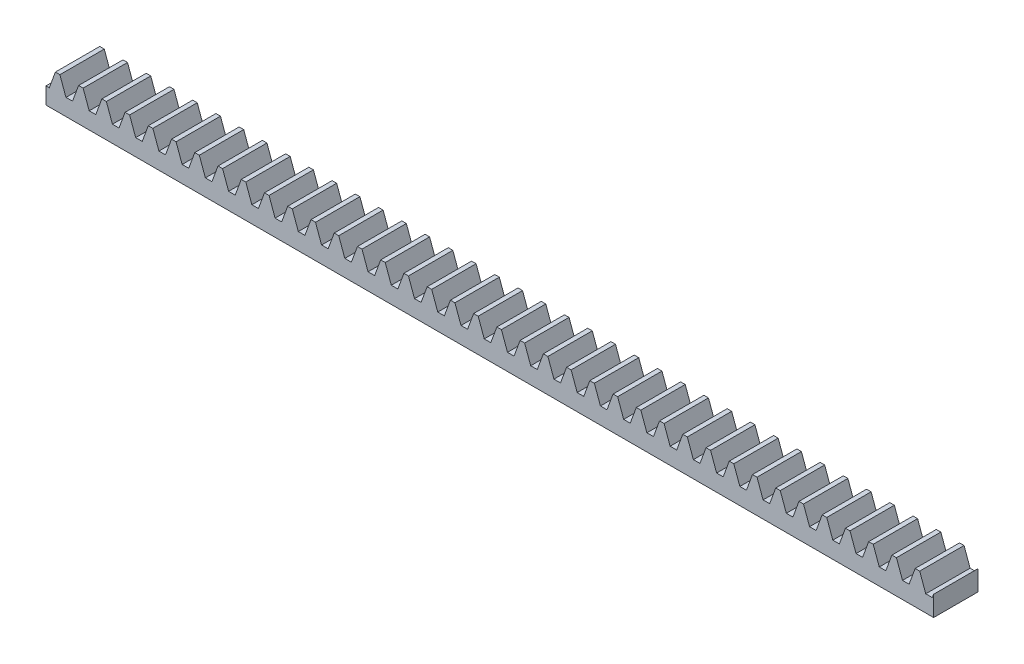
SolidWorks part; units mm, degrees
extrude "Blank" add sketch "BlankSke" against normal blind 6
sketch "BlankSke" plane through (0, 0, 0) normal (0, 0, 1) x (1, 0, 0)
  line L1 (0, 0) -> (120, 0)
  line L2 (0, 0) -> (0, 4.5)
  line L3 (0, 4.5) -> (120, 4.5)
  line L4 (120, 0) -> (120, 4.5)
  dimension "Length" = 120
  dimension "Blank_height" = 4.5
ref_plane "Plane1" through (0, 0, 0) normal (0, 0, 1) x (1, 0, 0)
ref_plane "Plane2" through (0, 0, 0) normal (0, 1, 0) x (1, 0, 0)
ref_plane "Plane3" through (0, 0, 0) normal (1, 0, 0) x (0, 0, -1)
sketch "HoldingSke" plane through (0, 0, 0) normal (0, 1, 0) x (1, 0, 0)
  line L0 (0, 0) -> (0.1392, 0.9903)
  line L1 (-15, 0) -> (100, 0) construction
  line L2 (0, 0) -> (-2.1039, 2.3779)
  line L3 (0, 0) -> (-11.863, 4.5341)
  line L4 (0, 0) -> (6.6156, 5.5511)
  line L5 (0, 0) -> (-23.7986, -8.8762)
  line L6 (0, 0) -> (-10.5278, -7.1032)
  line L9 (-71.009, 38.7566) -> (41.7541, 79.799)
  line L10 (-76.2, 3.3779) -> (-72.7, 3.3779)
  line L11 (0, 0) -> (-6, 0)
  line L12 (-76.2, 101.6) -> (-76.162, 101.6)
  line L13 (24.9733, 27.94) -> (52.9518, 28.4284)
  line L14 (24.9733, 27.94) -> (24.9743, 27.94)
  line L15 (24.9733, 27.94) -> (100.4006, 29.5858)
  circle A0 centre (0, 0) radius 19.05
  circle A1 centre (0, 0) radius 1.75
  circle A2 centre (0, 0) radius 12.7
  dimension "MPH" = 3.5
  dimension "Diameter" = 38.1
  dimension "Num_teeth" = 40
  dimension "Pitch" = 1
  dimension "Show_teeth" = 998
  dimension "Thickness" = 12.7
  dimension "Ap" = 20
  dimension "Pitch_height" = 3.5
  dimension "Width" = 6
  dimension "Backlash" = 0.038
  dimension "Addendum_fac" = 1
  dimension "Dedendum_fac" = 1.25
  dimension "Clearance_fac" = 0.25
  dimension "Dedendum_add" = 0.001
  dimension "Length" = 120
  dimension "Module" = 1
sketch "TooCutSkeIll" plane through (0, 0, 0) normal (0, 0, 1) x (1, 0, 0)
  line L0 (-1.2538, 4.4737) -> (-0.5045, 2.4152)
  line L1 (-0.2687, 2.25) -> (0.2687, 2.25)
  line L2 (0.5045, 2.4152) -> (1.2538, 4.4737)
  line L3 (120, 4.5) -> (0, 4.5) construction
  line L4 (0, 0) -> (0, 64.897) construction
  line L5 (-13.208, 3.5) -> (12.954, 3.5) construction
  line L6 (0, 0) -> (120, 0) construction
  line L7 (0.8994, 3.5) -> (0.8994, 48.7463) construction
  line L8 (-0.8994, 3.5) -> (-0.8994, 48.7463) construction
  line L9 (1.2914, 4.5) -> (1.2914, 4.5254)
  line L10 (-1.2914, 4.5) -> (-1.2914, 4.5254)
  line L11 (-1.2914, 4.5254) -> (1.2914, 4.5254)
  arc A0 (0.2687, 2.25) -> (0.5045, 2.4152) centre (0.2687, 2.501) ccw
  arc A1 (-0.5045, 2.4152) -> (-0.2687, 2.25) centre (-0.2687, 2.501) ccw
  arc A2 (1.2914, 4.5) -> (1.2538, 4.4737) centre (1.2914, 4.46) ccw
  arc A3 (-1.2538, 4.4737) -> (-1.2914, 4.5) centre (-1.2914, 4.46) ccw
  dimension "Pitch_height" = 3.5
  dimension "Addendum_plus" = 1.0254
  dimension "Pressure_angle" = 20
  dimension "Gap_width" = 1.7988
  dimension "Dedendum" = 1.25
extrude "ToothCutIll" [suppressed] cut sketch "TooCutSkeIll" against normal through all
sketch "TooCutSkeSim" plane through (0, 0, 0) normal (0, 0, 1) x (1, 0, 0)
  line L0 (0.4444, 2.25) -> (-0.4444, 2.25)
  line L1 (1.2726, 4.5254) -> (0.4444, 2.25)
  line L2 (0, 17.4625) -> (0, 53.467) construction
  line L3 (1.2726, 4.5254) -> (-1.2726, 4.5254)
  line L6 (-1.2726, 4.5254) -> (-0.4444, 2.25)
  line L9 (-0.8994, 3.5) -> (0.8994, 3.5) construction
  line L10 (0, 0) -> (120, 0) construction
  line L11 (0.8994, 3.5) -> (0.8994, 53.467) construction
  line L12 (-0.8994, 3.5) -> (-0.8994, 53.467) construction
  dimension "Pitch_height" = 3.5
  dimension "Addendum_plus" = 1.0254
  dimension "Pressure_angle" = 20
  dimension "Gap_width" = 1.7988
  dimension "Dedendum" = 1.25
extrude "ToothCutSim" cut sketch "TooCutSkeSim" against normal through all
pattern_linear "TeethCuts" count 39 spacing 3.1416 along (1, 0, 0) of "ToothCutIll", "ToothCutSim"
equation "' \"Module@HoldingSke\" = 6.35"
equation "' \"Num_teeth@HoldingSke\" = 12"
equation "' \"Ap@HoldingSke\" =  20"
equation "' \"Ap@HoldingSke\" = 20"
equation "' \"Width@HoldingSke\" = 0.25 * 25.4"
equation "' \"Show_teeth@HoldingSke\" = 500"
equation "' \"Backlash@HoldingSke\" = 0.009 * 25.4"
equation "' \"Addendum_fac@HoldingSke\" = 1.0"
equation "' \"Dedendum_fac@HoldingSke\" = 1.25"
equation "' \"Dedendum_add@HoldingSke\" = 0.00005 * 25.4"
equation "' \"Clearance_fac@HoldingSke\" = 0.25"
equation "' \"Pitch_height@HoldingSke\" = 1 * 25.4"
equation "' \"Length@HoldingSke\" = 4.71 * 25.4"
equation "\"Pitch@HoldingSke\" = 1 / \"Module@HoldingSke\""
equation "\"MPH@HoldingSke\" = \"Dedendum_fac@HoldingSke\" / \"Pitch@HoldingSke\" + 2 * \"Dedendum_add@HoldingSke\" + 0.002 * 25.4"
equation "\"MPH@HoldingSke\" = ((sgn( \"MPH@HoldingSke\" - \"Pitch_height@HoldingSke\")+1)*( \"MPH@HoldingSke\" - \"Pitch_height@HoldingSke\"))/2 + \"Pitch_height@HoldingSke\""
equation "\"Blank_height@BlankSke\" = \"Pitch_height@HoldingSke\" + \"Addendum_fac@HoldingSke\"  / \"Pitch@HoldingSke\" "
equation "\"Length@BlankSke\" =  \"Length@HoldingSke\""
equation "\"Face_width@Blank\" = \"Width@HoldingSke\""
equation "\"Pressure_angle@TooCutSkeIll\" = \"Ap@HoldingSke\""
equation "\"Addendum_plus@TooCutSkeIll\" =  \"Addendum_fac@HoldingSke\"  / \"Pitch@HoldingSke\" + 0.001 *25.4"
equation "\"Dedendum@TooCutSkeIll\" = \"Dedendum_fac@HoldingSke\"  / \"Pitch@HoldingSke\""
equation "\"Pitch_height@TooCutSkeIll\" =  \"MPH@HoldingSke\""
equation "\"Gap_width@TooCutSkeIll\" = 3.14159265 / 2 / \"Pitch@HoldingSke\" + 6 * \"Backlash@HoldingSke\""
equation "\"Pressure_angle@TooCutSkeSim\" = \"Ap@HoldingSke\""
equation "\"Addendum_plus@TooCutSkeSim\" =  \"Addendum_fac@HoldingSke\"  / \"Pitch@HoldingSke\" + 0.001 * 25.4"
equation "\"Dedendum@TooCutSkeSim\" = \"Dedendum_fac@HoldingSke\"  / \"Pitch@HoldingSke\""
equation "\"Pitch_height@TooCutSkeSim\" =  \"MPH@HoldingSke\""
equation "\"Gap_width@TooCutSkeSim\" = 3.14159265 / 2 / \"Pitch@HoldingSke\" + 6 * \"Backlash@HoldingSke\""
equation "\"Root_fillet@TooCutSkeIll\" = \"Clearance_fac@HoldingSke\" / \"Pitch@HoldingSke\" + \"Dedendum_add@HoldingSke\""
equation "\"Break_rad@TooCutSkeIll\" = 0.02 / \"Pitch@HoldingSke\" * 2"
equation "\"Linear_pitch@TeethCuts\" = 3.14159265 / \"Pitch@HoldingSke\""
equation "\"Num_teeth@HoldingSke\" = int( ( \"Length@HoldingSke\" + 0 ) / (3.14159265 / \"Pitch@HoldingSke\")) + 0.9999  + 1"
equation " \"Num_teeth@TeethCuts\" = int( \"Show_teeth@HoldingSke\" ) + 1"
equation " \"Num_teeth@TeethCuts\" = ((sgn( \"Num_teeth@TeethCuts\" - \"Num_teeth@HoldingSke\" )-1)*( \"Num_teeth@TeethCuts\" - \"Num_teeth@HoldingSke\" ))/-2+ \"Num_teeth@HoldingSke\""
equation " \"Num_teeth@TeethCuts\" = ((sgn( \"Num_teeth@TeethCuts\" - 2.0)+1)*( \"Num_teeth@TeethCuts\" - 2.0))/2 +2.0"
